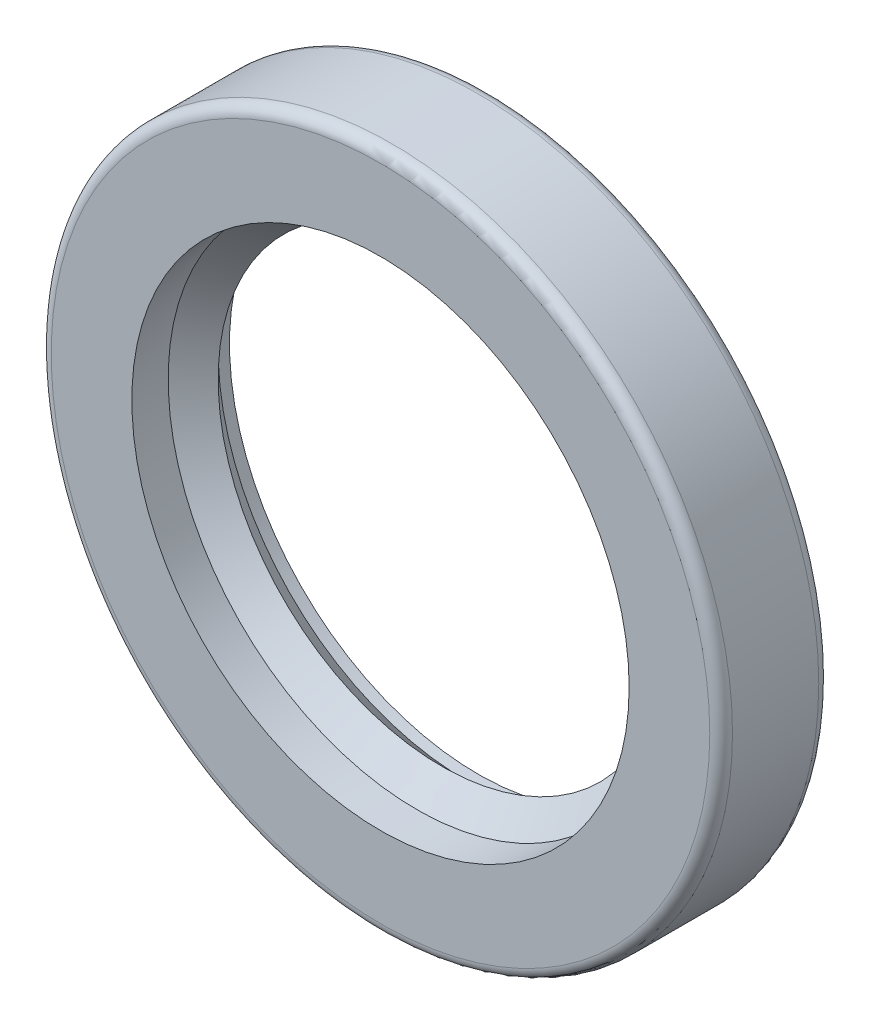
SolidWorks part; units mm, degrees
ref_plane "Front" through (0, 0, 0) normal (0, 0, 1) x (1, 0, 0)
ref_plane "Top" through (0, 0, 0) normal (0, 1, 0) x (1, 0, 0)
ref_plane "Right" through (0, 0, 0) normal (1, 0, 0) x (0, 0, -1)
sketch "Sketch1" plane through (0, 0, 0) normal (1, 0, 0) x (0, 0, -1)
  line L0 (0, 0) -> (26.9806, 0) construction
  line L1 (0, 13.9065) -> (0, 18.415)
  line L2 (0.635, 19.05) -> (5.461, 19.05)
  line L3 (6.096, 18.415) -> (6.096, 17.145)
  line L4 (6.096, 17.145) -> (2.032, 17.145)
  line L5 (2.032, 17.145) -> (2.032, 15.24)
  line L6 (2.032, 15.24) -> (2.413, 15.24)
  line L7 (4.445, 15.24) -> (5.461, 15.24)
  line L8 (5.461, 15.24) -> (5.461, 13.9065)
  line L9 (5.461, 13.9065) -> (4.826, 13.9065)
  line L10 (4.826, 13.9065) -> (3.429, 12.5095)
  line L11 (3.429, 12.5095) -> (2.032, 13.9065)
  line L12 (2.032, 13.9065) -> (0, 13.9065)
  arc A0 (2.413, 15.24) -> (4.445, 15.24) centre (3.429, 15.24) cw
  arc A1 (5.461, 19.05) -> (6.096, 18.415) centre (5.461, 18.415) cw
  arc A2 (0, 18.415) -> (0.635, 19.05) centre (0.635, 18.415) cw
  point P19 (6.096, 19.05)
  point P22 (0, 19.05)
  dimension "D10" = 1.016
  dimension "D11" = 0.635
  dimension "D1" = 45
  dimension "D2" = 38.1
  dimension "D3" = 27.813
  dimension "D4" = 30.48
  dimension "D5" = 34.29
  dimension "D6" = 25.019
  dimension "D7" = 6.096
  dimension "D8" = 5.461
  dimension "D9" = 2.032
revolve "Revolve1" add sketch "Sketch1" angle 360 about L0
